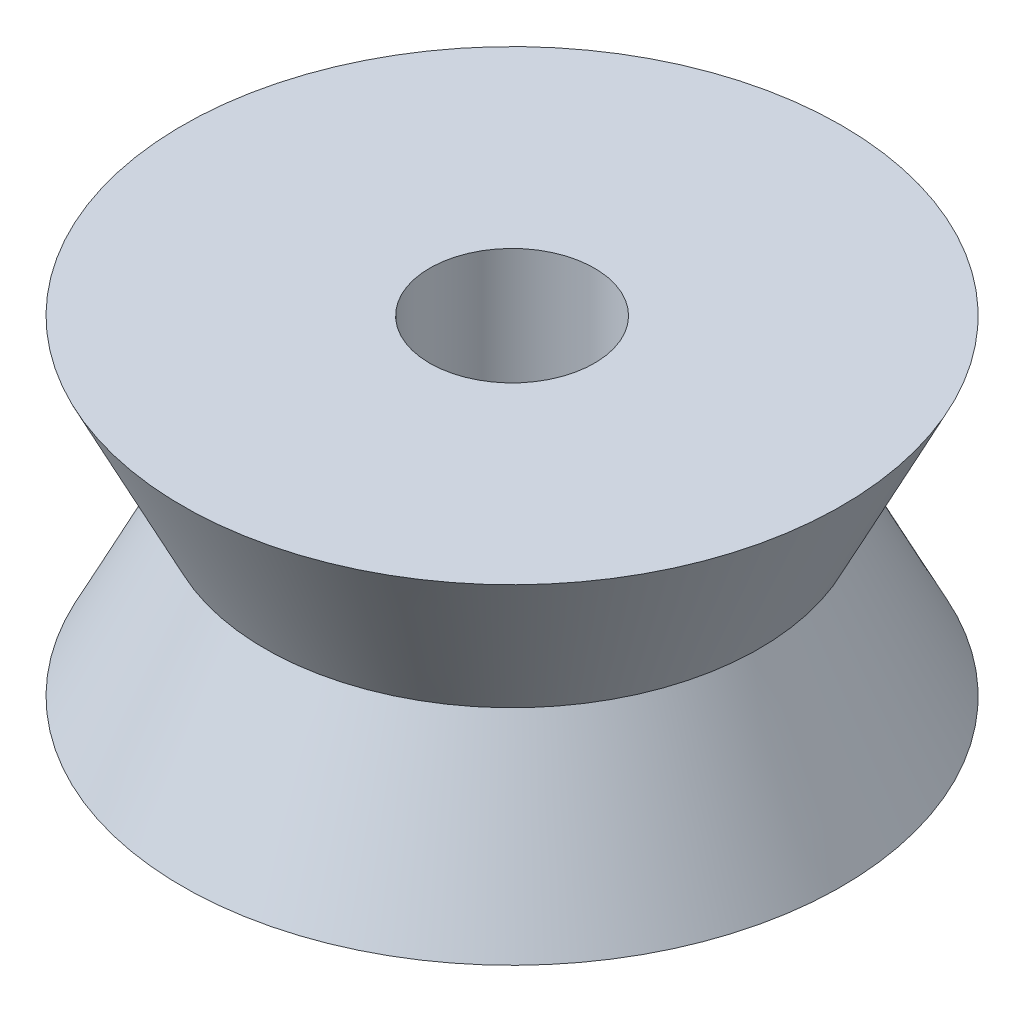
SolidWorks part; units mm, degrees
ref_plane "Front Plane" through (0, 0, 0) normal (0, 0, 1) x (1, 0, 0)
ref_plane "Top Plane" through (0, 0, 0) normal (0, 1, 0) x (1, 0, 0)
ref_plane "Right Plane" through (0, 0, 0) normal (1, 0, 0) x (0, 0, -1)
sketch "Sketch1" plane through (0, 0, 0) normal (0, 0, 1) x (1, 0, 0)
  line L0 (-20, 20) -> (-15, 10)
  line L1 (0, 0) -> (-20, 0)
  line L2 (0, 0) -> (0, 20)
  line L3 (0, 20) -> (-20, 20)
  line L5 (-15, 10) -> (-20, 0)
  dimension "D1" = 20
  dimension "D2" = 20
  dimension "D3" = 10
  dimension "D4" = 20
  dimension "D5" = 5
revolve "Revolve1" add sketch "Sketch1" angle 360 about L2
sketch "Sketch2" plane through (0, 20, 0) normal (0, 1, 0) x (1, 0, 0)
  circle A0 centre (0, 0) radius 5
  dimension "D1" = 10
extrude "Cut-Extrude1" cut sketch "Sketch2" against normal through all
